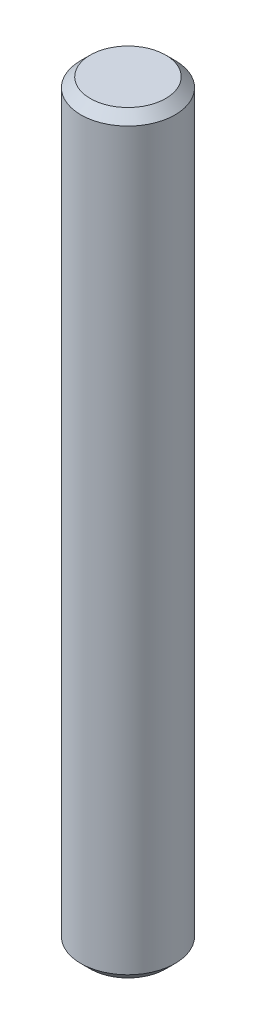
SolidWorks part; units mm, degrees
ref_plane "前视基准面" through (0, 0, 0) normal (0, 0, 1) x (1, 0, 0)
ref_plane "上视基准面" through (0, 0, 0) normal (0, 1, 0) x (1, 0, 0)
ref_plane "右视基准面" through (0, 0, 0) normal (1, 0, 0) x (0, 0, -1)
other "Configuration Table"
sketch "草图1" plane through (0, 0, 0) normal (0, 0, 1) x (1, 0, 0)
  line L0 (0, 17.9143) -> (0, -10.0949) construction
  line L1 (0, 40) -> (5, 40)
  line L2 (5, 40) -> (5, 30)
  line L4 (5, 30) -> (5, -30)
  line L6 (5, -30) -> (5, -40)
  line L7 (5, -40) -> (0, -40)
  line L8 (0, 0) -> (25.4592, 0) construction
  line L9 (0, 40) -> (0, -40)
  dimension "D1" = 5
  dimension "D3" = 60
  dimension "D4" = 10
  dimension "D5" = 10
revolve "旋转1" add sketch "草图1" angle 360 about L9
chamfer "倒角1" distance 1 angle 45 2 edges at (-5, -40, 0) (-5, 40, 0)
